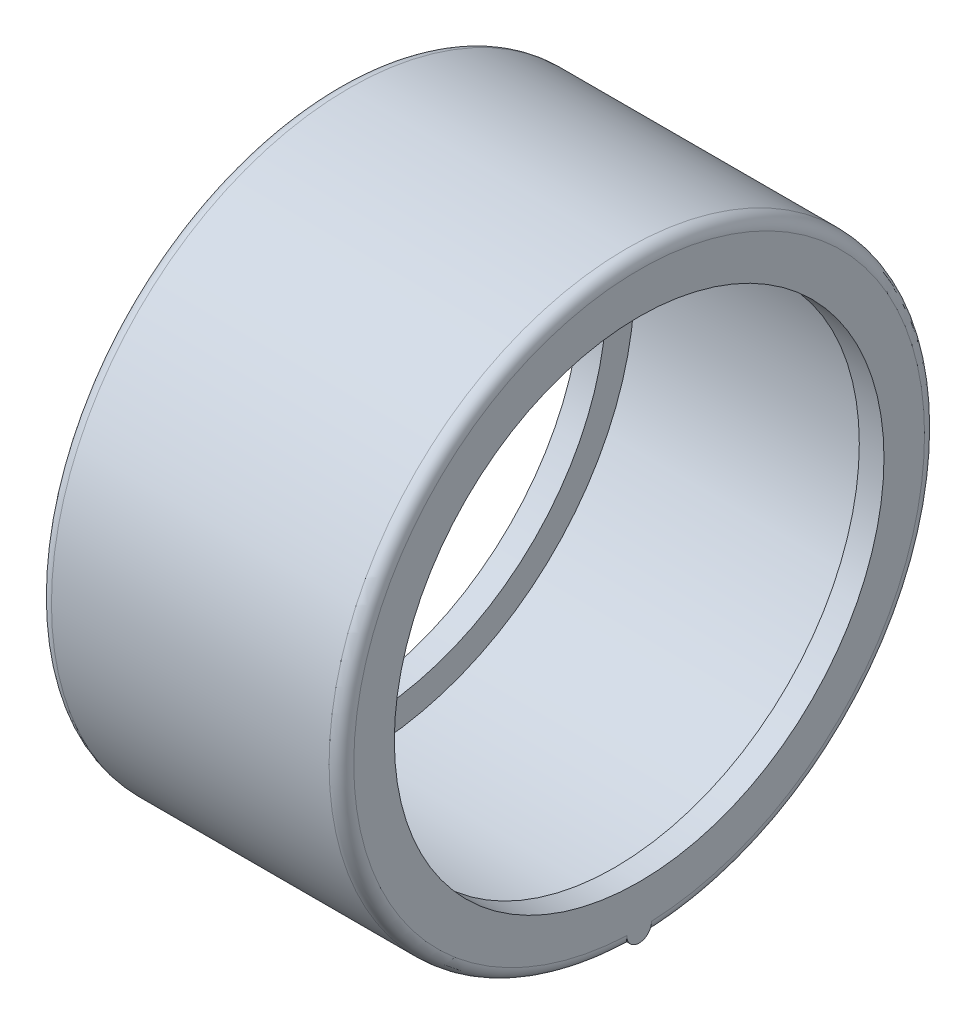
SolidWorks part; units mm, degrees
material "BUTYL"
ref_plane "Piano frontale" through (0, 0, 0) normal (0, 0, 1) x (1, 0, 0)
ref_plane "Piano superiore" through (0, 0, 0) normal (0, 1, 0) x (1, 0, 0)
ref_plane "Piano destro" through (0, 0, 0) normal (1, 0, 0) x (0, 0, -1)
sketch "Schizzo1" plane through (0, 0, 0) normal (0, 0, 1) x (1, 0, 0)
  line L0 (0, 0) -> (0, 42.875)
  line L1 (0, 42.875) -> (-245, 42.875)
  line L2 (-245, 42.875) -> (-245, 0)
  line L3 (-245, 0) -> (-225, 0)
  line L4 (-225, 0) -> (-225, 22.875)
  line L5 (-225, 22.875) -> (-20, 22.875)
  line L6 (-20, 22.875) -> (-20, 0)
  line L7 (-20, 0) -> (0, 0)
  line L8 (-137.6608, -198.425) -> (-433.0909, -198.425) construction
  dimension "D1" = 245
  dimension "D2" = 42.875
  dimension "D3" = 20
  dimension "D4" = 20
  dimension "D5" = 20
  dimension "D6" = 42.875
  dimension "D7" = 241.3
revolve "Rivoluzione1" add sketch "Schizzo1" angle 360 about L8
fillet "Raccordo1" radius 10 2 edges at (0, 42.875, 0) (-245, 42.875, 0)
ref_plane "Piano1" through (-10, 0, 0) normal (1, 0, 0) x (0, 0, -1)
sketch "Schizzo2" plane through (0, 0, 0) normal (1, 0, 0) x (0, 0, -1)
  circle A0 centre (0, -429.725) radius 10
  circle A2 centre (0, -198.425) radius 241.3 construction
extrude "Estrusione-Estrusione1" add sketch "Schizzo2" against normal up to surface (245 mm away) up to face at (-245, -429.725, 0)
ref_plane "Piano2" through (-235, 0, 0) normal (1, 0, 0) x (0, 0, -1)
